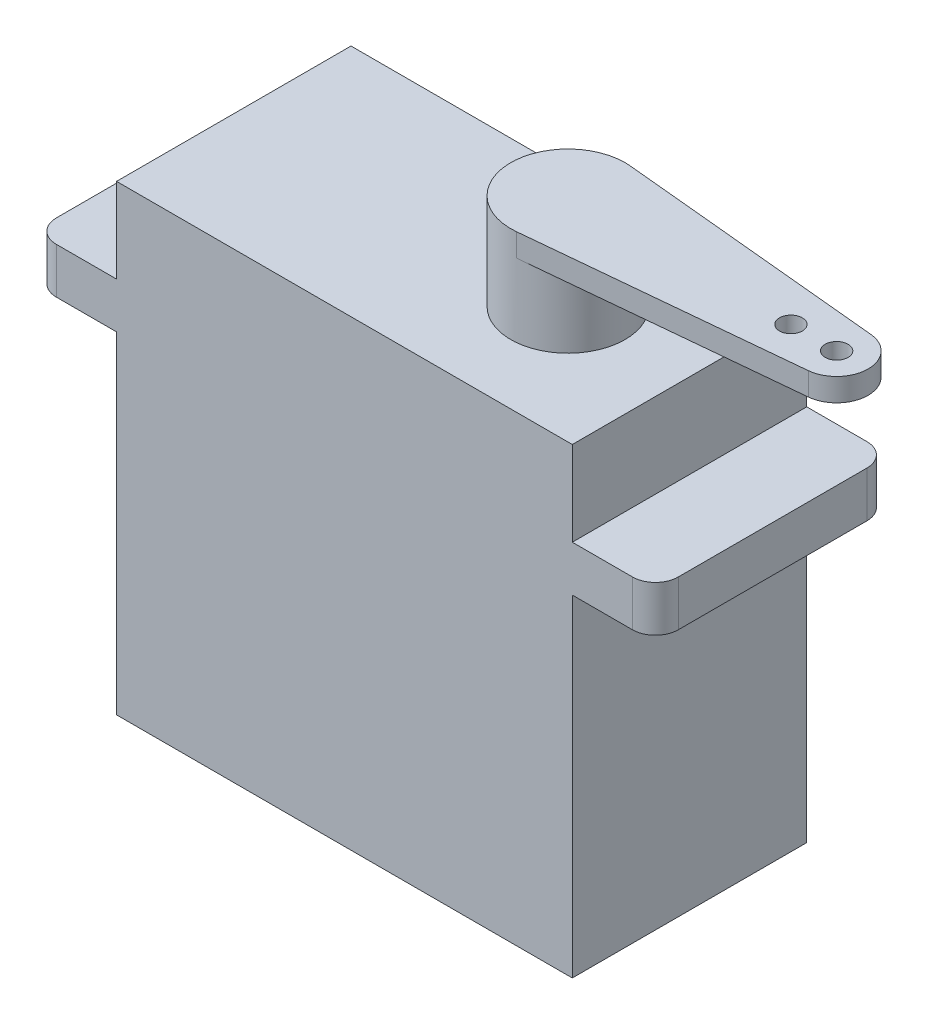
SolidWorks part; units mm, degrees
material "Default"
ref_plane "Front Plane" through (0, 0, 0) normal (0, 0, 1) x (1, 0, 0)
ref_plane "Top Plane" through (0, 0, 0) normal (0, 1, 0) x (1, 0, 0)
ref_plane "Right Plane" through (0, 0, 0) normal (1, 0, 0) x (0, 0, -1)
sketch "Sketch2" plane through (0, 0, 0) normal (0, 1, 0) x (1, 0, 0)
  line L1 (0, 0) -> (39.85, 0)
  line L2 (0, 0) -> (0, 20.5)
  line L3 (0, 20.5) -> (39.85, 20.5)
  line L4 (39.85, 0) -> (39.85, 20.5)
  dimension "D1" = 39.85
  dimension "D2" = 20.5
extrude "Boss-Extrude1" add sketch "Sketch2" along normal blind 40.4
sketch "Sketch3" plane through (0, 0, 0) normal (0, 1, 0) x (1, 0, 0)
  line L0 (0, 20.5) -> (0, 0) construction
  line L1 (-7.265, 0) -> (47.115, 0)
  line L2 (-7.265, 0) -> (-7.265, 20.5)
  line L3 (-7.265, 20.5) -> (47.115, 20.5)
  line L4 (47.115, 0) -> (47.115, 20.5)
  line L5 (39.85, 20.5) -> (0, 20.5) construction
  line L6 (39.85, 0) -> (39.85, 20.5) construction
  point P6 (0, 10.25)
  point P7 (-7.265, 10.25)
  point P10 (19.925, 20.5)
  point P11 (19.925, 20.5)
  dimension "D1" = 20.5
  dimension "D2" = 54.38
  dimension "D3" = 7.265
  dimension "D4" = 7.265
extrude "Boss-Extrude2" add sketch "Sketch3" along normal blind 4 from offset 29
ref_plane "Plane1" through (20, 0, 0) normal (1, 0, 0) x (0, 0, -1)
fillet "Fillet1" radius 2 4 edges at (47.115, 31, -20.5) (47.115, 31, 0) (-7.265, 31, 0) (-7.265, 31, -20.5)
sketch "Sketch5" plane through (0, 40.4, 0) normal (0, 1, 0) x (1, 0, 0)
  line L0 (39.85, 20.5) -> (39.85, 0) construction
  line L2 (47.115, 2) -> (47.115, 18.5) construction
  circle A0 centre (29.215, 10.25) radius 5
  point P5 (39.85, 10.25)
  dimension "D1" = 10
  dimension "D2" = 17.9
extrude "Boss-Extrude3" add sketch "Sketch5" along normal blind 8.4
sketch "Sketch6" plane through (0, 48.8, 0) normal (0, 1, 0) x (1, 0, 0)
  line L0 (29.6937, 15.227) -> (52.9783, 12.9874)
  line L1 (29.6937, 5.273) -> (52.9783, 7.5126)
  arc A0 (29.6937, 15.227) -> (29.6937, 5.273) centre (29.215, 10.25) ccw
  arc A1 (52.9783, 7.5126) -> (52.9783, 12.9874) centre (52.715, 10.25) ccw
  dimension "D1" = 10
  dimension "D2" = 5.5
  dimension "D3" = 23.5
extrude "Boss-Extrude4" add sketch "Sketch6" against normal blind 2
sketch "Sketch7" plane through (0, 48.8, 0) normal (0, 1, 0) x (1, 0, 0)
  circle A0 centre (52.715, 10.25) radius 1
  circle A1 centre (48.715, 10.25) radius 1
  arc A2 (29.6937, 15.227) -> (29.6937, 5.273) centre (29.215, 10.25) ccw construction
  dimension "D1" = 2
  dimension "D2" = 2
  dimension "D3" = 19.5
extrude "Cut-Extrude1" cut sketch "Sketch7" against normal blind 2
